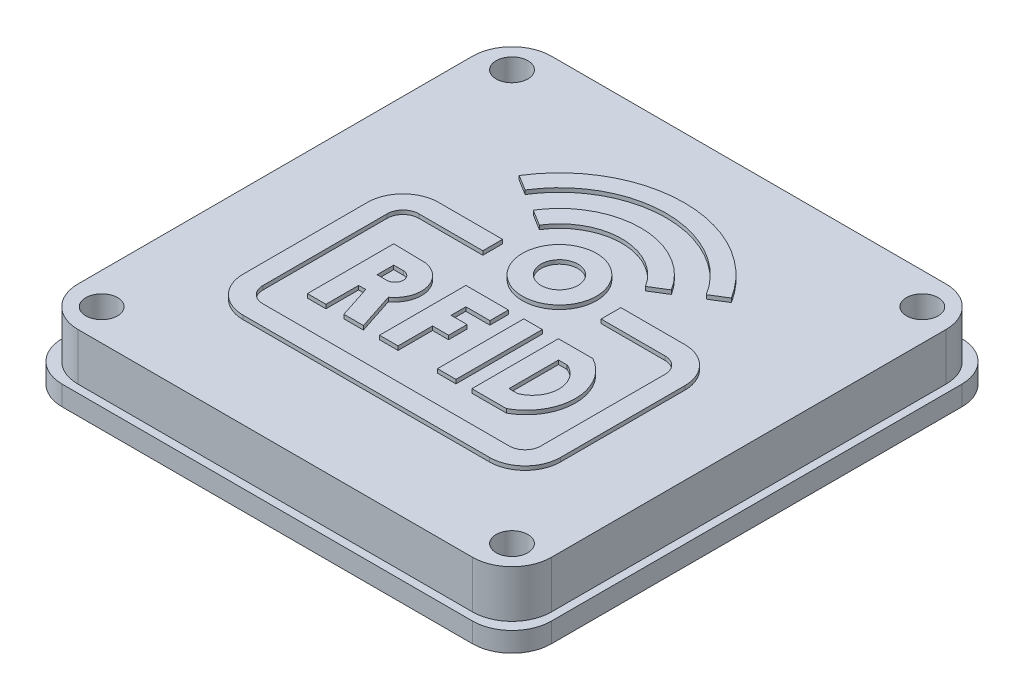
SolidWorks part; units mm, degrees
ref_plane "Front Plane" through (0, 0, 0) normal (0, 0, 1) x (1, 0, 0)
ref_plane "Top Plane" through (0, 0, 0) normal (0, 1, 0) x (1, 0, 0)
ref_plane "Right Plane" through (0, 0, 0) normal (1, 0, 0) x (0, 0, -1)
sketch "Sketch1" plane through (0, 0, 0) normal (0, 1, 0) x (1, 0, 0)
  line L1 (-60, 60) -> (60, 60)
  line L2 (-60, 60) -> (-60, -60)
  line L3 (-60, -60) -> (60, -60)
  line L4 (60, 60) -> (60, -60)
  line L5 (-60, 60) -> (60, -60) construction
  line L6 (-60, -60) -> (60, 60) construction
  point P0 (0, 0)
  dimension "D1" = 120
  dimension "D2" = 120
extrude "Boss-Extrude1" add sketch "Sketch1" along normal blind 17
shell "Shell1" thickness 3
sketch "Sketch2" plane through (0, 0, 0) normal (0, -1, 0) x (1, 0, 0)
  line L0 (60, -60) -> (-60, -60) construction
  line L1 (60, 60) -> (60, -60) construction
  line L2 (-60, 60) -> (60, 60) construction
  line L3 (-60, -60) -> (-60, 60) construction
  line L4 (60, -60) -> (-60, -60)
  line L5 (60, 60) -> (60, -60)
  line L6 (-60, 60) -> (60, 60)
  line L7 (-60, -60) -> (-60, 60)
  line L8 (-62, -62) -> (-62, 62)
  line L9 (-62, 62) -> (62, 62)
  line L10 (62, 62) -> (62, -62)
  line L11 (62, -62) -> (-62, -62)
  dimension "D1" = 2
extrude "Boss-Extrude2" add sketch "Sketch2" against normal blind 5
sketch "Sketch3" plane through (0, 17, 0) normal (0, 1, 0) x (1, 0, 0)
  line L0 (0, 60) -> (0, -60) construction
  line L1 (60, 60) -> (-60, 60) construction
  line L2 (-60, -60) -> (60, -60) construction
  line L3 (-60, 0) -> (60, 0) construction
  line L4 (-60, 60) -> (-60, -60) construction
  line L5 (60, 60) -> (60, -60) construction
  line L6 (-60, 52) -> (-52, 52) construction
  line L19 (-60, -60) -> (-60, 60) construction
  line L22 (-52, 52) -> (-52, 60) construction
  circle A4 centre (-52, 52) radius 4.02
  circle A5 centre (52, 52) radius 4.02
  circle A6 centre (52, -52) radius 4.02
  circle A7 centre (-52, -52) radius 4.02
  dimension "D1" = 8.04
  dimension "D3" = 8
  dimension "D2" = 8
sketch "Sketch4" plane through (0, 14, 0) normal (0, -1, 0) x (1, 0, 0)
  line L0 (-52, 60) -> (-52, 52) construction
  line L1 (60, 60) -> (-60, 60) construction
  line L10 (-52, 52) -> (-60, 52) construction
  line L11 (-60, 60) -> (-60, -60) construction
  line L12 (-57, 42.98) -> (-57, 57)
  line L14 (-57, 57) -> (-42.98, 57)
  line L16 (-55, 44.98) -> (-52, 44.98)
  line L17 (-44.98, 52) -> (-44.98, 55)
  line L18 (0, 60) -> (0, -60) construction
  line L19 (57, 42.98) -> (57, 57)
  line L20 (60, 0) -> (-60, 0) construction
  line L21 (55, 44.98) -> (52, 44.98)
  line L22 (44.98, 52) -> (44.98, 55)
  line L23 (57, 57) -> (42.98, 57)
  line L24 (55, -44.98) -> (52, -44.98)
  line L25 (44.98, -52) -> (44.98, -55)
  line L26 (57, -57) -> (42.98, -57)
  line L27 (57, -42.98) -> (57, -57)
  line L28 (-57, -42.98) -> (-57, -57)
  line L29 (-55, -44.98) -> (-52, -44.98)
  line L30 (-44.98, -52) -> (-44.98, -55)
  line L31 (-57, -57) -> (-42.98, -57)
  circle A8 centre (-52, 52) radius 4.02
  arc A9 (-52, 44.98) -> (-44.98, 52) centre (-52, 52) ccw
  arc A10 (-57, 42.98) -> (-55, 44.98) centre (-55, 42.98) cw
  arc A11 (-42.98, 57) -> (-44.98, 55) centre (-42.98, 55) ccw
  circle A12 centre (-52, 52) radius 7.02 construction
  arc A13 (57, 42.98) -> (55, 44.98) centre (55, 42.98) ccw
  arc A14 (52, 44.98) -> (44.98, 52) centre (52, 52) cw
  arc A15 (42.98, 57) -> (44.98, 55) centre (42.98, 55) cw
  circle A16 centre (52, 52) radius 4.02
  arc A17 (57, -42.98) -> (55, -44.98) centre (55, -42.98) cw
  arc A18 (52, -44.98) -> (44.98, -52) centre (52, -52) ccw
  arc A19 (42.98, -57) -> (44.98, -55) centre (42.98, -55) ccw
  circle A20 centre (52, -52) radius 4.02
  arc A21 (-57, -42.98) -> (-55, -44.98) centre (-55, -42.98) ccw
  arc A22 (-52, -44.98) -> (-44.98, -52) centre (-52, -52) cw
  arc A23 (-42.98, -57) -> (-44.98, -55) centre (-42.98, -55) cw
  circle A24 centre (-52, -52) radius 4.02
  dimension "D1" = 8
  dimension "D4" = 3
  dimension "D3" = 8.04
  dimension "D5" = 2
  dimension "D2" = 8
extrude "Boss-Extrude3" add sketch "Sketch4" along normal blind 14
extrude "Cut-Extrude1" cut sketch "Sketch3" against normal blind 3
fillet "Fillet1" radius 10 8 edges at (-60, 11, -60) (-62, 2.5, -62) (-60, 11, 60) (-62, 2.5, 62) (62, 2.5, -62) (60, 11, -60) (62, 2.5, 62) (60, 11, 60)
sketch "Sketch8" plane through (0, 17, 0) normal (0, 1, 0) x (1, 0, 0)
  point P0 (0, -31.9271)
  point P2 (0, 0)
  line B0 (-25.73, 30.2815) -> (-26.8861, 28.7192)
  line B1 (-26.8861, 28.7192) -> (-24.9958, 27.5006)
  line B2 (24.996, 27.485) -> (26.8863, 28.7036)
  line B3 (26.8863, 28.7036) -> (25.6834, 30.3127)
  line B4 (15.7787, 21.5173) -> (17.6534, 22.7202)
  line B5 (17.6534, 22.7202) -> (17.4035, 23.1264)
  line B6 (-2.1871, 32.2655) -> (-2.187, 32.2655)
  line B7 (39.9622, -11.7272) -> (39.9154, 4.0045)
  line B8 (39.9154, 4.0045) -> (39.4935, 5.2699)
  line B9 (23.2462, 12.3156) -> (14.9976, 12.3781)
  line B10 (14.9976, 12.3781) -> (14.9976, 10.0347)
  line B11 (14.9976, 10.0347) -> (14.9976, 7.6913)
  line B12 (14.9976, 7.6913) -> (23.0119, 7.6445)
  line B13 (23.0119, 7.6445) -> (31.0105, 7.5976)
  line B14 (31.0105, 7.5976) -> (32.026, 7.1133)
  line B15 (34.8068, 4.3951) -> (35.2286, 3.5358)
  line B16 (35.2286, 3.5358) -> (35.2286, -12.1647)
  line B17 (35.2286, -12.1647) -> (35.2286, -27.8653)
  line B18 (35.2286, -27.8653) -> (34.713, -28.912)
  line B19 (32.0416, -31.5209) -> (31.1667, -31.9271)
  line B20 (31.1667, -31.9271) -> (0, -31.9271)
  line B21 (0, -31.9271) -> (-31.1667, -31.9271)
  line B22 (-31.1667, -31.9271) -> (-32.0259, -31.5209)
  line B23 (-34.713, -28.912) -> (-35.2286, -27.8653)
  line B24 (-35.2286, -27.8653) -> (-35.2286, -12.1647)
  line B25 (-35.2286, -12.1647) -> (-35.2286, 3.5358)
  line B26 (-35.2286, 3.5358) -> (-34.7911, 4.4263)
  line B27 (-32.0259, 7.1133) -> (-31.0105, 7.5976)
  line B28 (-31.0105, 7.5976) -> (-22.9962, 7.6445)
  line B29 (-22.9962, 7.6445) -> (-14.9975, 7.6913)
  line B30 (-14.9975, 7.6913) -> (-14.9975, 10.0347)
  line B31 (-14.9975, 10.0347) -> (-14.9975, 12.3625)
  line B32 (-14.9975, 12.3625) -> (-22.6837, 12.3468)
  line B33 (-31.1667, 12.2062) -> (-31.1666, 12.2063)
  line B34 (-27.8078, -13.102) -> (-27.8078, -24.0377)
  line B35 (-27.8078, -24.0377) -> (-25.4644, -24.0377)
  line B36 (-25.4644, -24.0377) -> (-23.121, -24.0377)
  line B37 (-23.121, -24.0377) -> (-23.121, -19.8977)
  line B38 (-23.121, -19.8977) -> (-23.121, -15.7578)
  line B39 (-23.121, -15.7578) -> (-22.2149, -15.7578)
  line B40 (-22.2149, -15.7578) -> (-21.3088, -15.7578)
  line B41 (-21.3088, -15.7578) -> (-19.9809, -19.8509)
  line B42 (-19.9809, -19.8509) -> (-18.653, -23.9596)
  line B43 (-18.653, -23.9596) -> (-16.1847, -24.0065)
  line B44 (-15.2942, -19.101) -> (-16.7627, -14.5705)
  line B45 (-16.7627, -14.5705) -> (-15.9815, -13.7894)
  line B46 (-24.152, -2.1663) -> (-27.8077, -2.1663)
  line B47 (-27.8077, -2.1663) -> (-27.8077, -13.102)
  line B48 (-21.715, -11.0711) -> (-23.1211, -11.0711)
  line B49 (-23.1211, -11.0711) -> (-23.1211, -8.9621)
  line B50 (-23.1211, -8.9621) -> (-23.1211, -6.853)
  line B51 (-23.1211, -6.853) -> (-21.8244, -6.853)
  line B52 (-9.5295, -13.102) -> (-9.5295, -24.0377)
  line B53 (-9.5295, -24.0377) -> (-7.1862, -24.0377)
  line B54 (-7.1862, -24.0377) -> (-4.8428, -24.0377)
  line B55 (-4.8428, -24.0377) -> (-4.8428, -19.6634)
  line B56 (-4.8428, -19.6634) -> (-4.8428, -15.2891)
  line B57 (-4.8428, -15.2891) -> (-2.8119, -15.2891)
  line B58 (-2.8119, -15.2891) -> (-0.781, -15.2891)
  line B59 (-0.781, -15.2891) -> (-0.781, -12.9457)
  line B60 (-0.781, -12.9457) -> (-0.781, -10.6023)
  line B61 (-0.781, -10.6023) -> (-2.8119, -10.6023)
  line B62 (-2.8119, -10.6023) -> (-4.8428, -10.6023)
  line B63 (-4.8428, -10.6023) -> (-4.8428, -8.7277)
  line B64 (-4.8428, -8.7277) -> (-4.8428, -6.853)
  line B65 (-4.8428, -6.853) -> (-1.7964, -6.853)
  line B66 (-1.7964, -6.853) -> (1.25, -6.853)
  line B67 (1.25, -6.853) -> (1.25, -4.5096)
  line B68 (1.25, -4.5096) -> (1.25, -2.1662)
  line B69 (1.25, -2.1662) -> (-4.1397, -2.1662)
  line B70 (-4.1397, -2.1662) -> (-9.5295, -2.1662)
  line B71 (-9.5295, -2.1662) -> (-9.5295, -13.1019)
  line B72 (5.1555, -13.102) -> (5.1555, -24.0377)
  line B73 (5.1555, -24.0377) -> (7.4989, -24.0377)
  line B74 (7.4989, -24.0377) -> (9.8423, -24.0377)
  line B75 (9.8423, -24.0377) -> (9.8423, -13.102)
  line B76 (9.8423, -13.102) -> (9.8423, -2.1663)
  line B77 (9.8423, -2.1663) -> (7.4989, -2.1663)
  line B78 (7.4989, -2.1663) -> (5.1555, -2.1663)
  line B79 (5.1555, -2.1663) -> (5.1555, -13.102)
  line B80 (13.904, -13.102) -> (13.904, -24.0689)
  line B81 (13.904, -24.0689) -> (17.7784, -24.0065)
  line B82 (17.7784, -2.1976) -> (13.904, -2.1351)
  line B83 (13.904, -2.1351) -> (13.904, -13.102)
  line B84 (19.4188, -19.351) -> (18.5908, -19.351)
  line B85 (18.5908, -19.351) -> (18.5908, -13.0864)
  line B86 (18.5908, -13.0864) -> (18.5908, -6.8061)
  line B87 (18.5908, -6.8061) -> (19.8094, -6.8999)
  spline B88 degree 3 poles (-2.7338, 43.2012) (-12.1385, 42.217) (-20.2153, 37.6864) (-25.73, 30.2815) knots 0 0 0 0 0.071429 0.071429 0.071429 0.071429
  spline B89 degree 3 poles (-24.9958, 27.5006) (-23.9491, 26.8133) (-23.043, 26.2665) (-22.9805, 26.2665) knots 0.214286 0.214286 0.214286 0.214286 0.285714 0.285714 0.285714 0.285714
  spline B90 degree 3 poles (-22.9805, 26.2665) (-22.9024, 26.2665) (-22.4025, 26.8757) (-21.8557, 27.6257) knots 0.285714 0.285714 0.285714 0.285714 0.357143 0.357143 0.357143 0.357143
  spline B91 degree 3 poles (-21.8557, 27.6257) (-19.403, 31.0157) (-15.7161, 34.0152) (-11.6386, 35.968) knots 0.357143 0.357143 0.357143 0.357143 0.428571 0.428571 0.428571 0.428571
  spline B92 degree 3 poles (-11.6386, 35.968) (-0.0624, 41.5296) (14.0915, 38.0302) (21.7777, 27.7194) knots 0.428571 0.428571 0.428571 0.428571 0.5 0.5 0.5 0.5
  spline B93 degree 3 poles (21.7777, 27.7194) (22.3714, 26.9226) (22.9182, 26.2665) (22.9963, 26.2665) knots 0.5 0.5 0.5 0.5 0.571429 0.571429 0.571429 0.571429
  spline B94 degree 3 poles (22.9963, 26.2665) (23.0588, 26.2665) (23.9649, 26.8133) (24.996, 27.485) knots 0.571429 0.571429 0.571429 0.571429 0.642857 0.642857 0.642857 0.642857
  spline B95 degree 3 poles (25.6834, 30.3127) (20.6373, 37.0772) (13.3417, 41.514) (4.9993, 42.9044) knots 0.785714 0.785714 0.785714 0.785714 0.857143 0.857143 0.857143 0.857143
  spline B96 degree 3 poles (4.9993, 42.9044) (3.5776, 43.1387) (-1.4371, 43.3418) (-2.7338, 43.2012) knots 0.857143 0.857143 0.857143 0.857143 0.928571 0.928571 0.928571 0.928571
  spline B97 degree 3 poles (-2.187, 32.2655) (-6.905, 31.6718) (-11.2168, 29.6722) (-14.5131, 26.5008) knots 0 0 0 0 0.066667 0.066667 0.066667 0.066667
  spline B98 degree 3 poles (-14.5131, 26.5008) (-15.9191, 25.1417) (-17.747, 22.8452) (-17.5439, 22.689) knots 0.066667 0.066667 0.066667 0.066667 0.133333 0.133333 0.133333 0.133333
  spline B99 degree 3 poles (-17.5439, 22.689) (-17.1221, 22.3453) (-13.9351, 20.33) (-13.8101, 20.33) knots 0.133333 0.133333 0.133333 0.133333 0.2 0.2 0.2 0.2
  spline B100 degree 3 poles (-13.8101, 20.33) (-13.732, 20.33) (-13.279, 20.8299) (-12.8259, 21.4392) knots 0.2 0.2 0.2 0.2 0.266667 0.266667 0.266667 0.266667
  spline B101 degree 3 poles (-12.8259, 21.4392) (-10.7481, 24.1575) (-7.4362, 26.2821) (-3.8274, 27.2195) knots 0.266667 0.266667 0.266667 0.266667 0.333333 0.333333 0.333333 0.333333
  spline B102 degree 3 poles (-3.8274, 27.2195) (-1.7965, 27.735) (1.8123, 27.735) (3.8119, 27.2195) knots 0.333333 0.333333 0.333333 0.333333 0.4 0.4 0.4 0.4
  spline B103 degree 3 poles (3.8119, 27.2195) (7.452, 26.2665) (10.5296, 24.3137) (12.7011, 21.5798) knots 0.4 0.4 0.4 0.4 0.466667 0.466667 0.466667 0.466667
  spline B104 degree 3 poles (12.7011, 21.5798) (13.2167, 20.9393) (13.6853, 20.3768) (13.7634, 20.3612) knots 0.466667 0.466667 0.466667 0.466667 0.533333 0.533333 0.533333 0.533333
  spline B105 degree 3 poles (13.7634, 20.3612) (13.8416, 20.3299) (14.7477, 20.8455) (15.7787, 21.5173) knots 0.533333 0.533333 0.533333 0.533333 0.6 0.6 0.6 0.6
  spline B106 degree 3 poles (17.4035, 23.1264) (16.7629, 24.1106) (15.5288, 25.5479) (14.3571, 26.6414) knots 0.733333 0.733333 0.733333 0.733333 0.8 0.8 0.8 0.8
  spline B107 degree 3 poles (14.3571, 26.6414) (11.5294, 29.2972) (7.8425, 31.2032) (4.0619, 31.9687) knots 0.8 0.8 0.8 0.8 0.866667 0.866667 0.866667 0.866667
  spline B108 degree 3 poles (4.0619, 31.9687) (2.9058, 32.203) (-1.1404, 32.3905) (-2.1871, 32.2655) knots 0.866667 0.866667 0.866667 0.866667 0.933333 0.933333 0.933333 0.933333
  spline B109 degree 3 poles (4.4212, 20.2988) (2.3591, 21.3767) (-0.1249, 21.6735) (-2.312, 21.1111) knots 0.875 0.875 0.875 0.875 1 1 1 1
  spline B110 degree 3 poles (8.4049, 16.112) (7.6238, 17.7367) (5.9366, 19.5021) (4.4212, 20.2988) knots 0.75 0.75 0.75 0.75 0.875 0.875 0.875 0.875
  spline B111 degree 3 poles (9.3423, 11.4565) (9.4361, 13.2218) (9.1861, 14.4716) (8.4049, 16.112) knots 0.625 0.625 0.625 0.625 0.75 0.75 0.75 0.75
  spline B112 degree 3 poles (2.2654, 2.9111) (6.2335, 3.9109) (9.108, 7.379) (9.3423, 11.4565) knots 0.5 0.5 0.5 0.5 0.625 0.625 0.625 0.625
  spline B113 degree 3 poles (-2.2652, 2.9111) (-1.0779, 2.6142) (1.078, 2.6142) (2.2654, 2.9111) knots 0.375 0.375 0.375 0.375 0.5 0.5 0.5 0.5
  spline B114 degree 3 poles (-9.3421, 11.4565) (-9.1077, 7.379) (-6.2489, 3.9265) (-2.2652, 2.9111) knots 0.25 0.25 0.25 0.25 0.375 0.375 0.375 0.375
  spline B115 degree 3 poles (-6.6082, 18.5959) (-8.5922, 16.6275) (-9.4983, 14.2685) (-9.3421, 11.4565) knots 0.125 0.125 0.125 0.125 0.25 0.25 0.25 0.25
  spline B116 degree 3 poles (-2.312, 21.1111) (-4.0149, 20.658) (-5.2334, 19.955) (-6.6082, 18.5959) knots 0 0 0 0 0.125 0.125 0.125 0.125
  spline B117 degree 3 poles (-4.6554, 12.3625) (-4.421, 15.487) (-1.2966, 17.518) (1.6092, 16.4244) knots 0.8 0.8 0.8 0.8 1 1 1 1
  spline B118 degree 3 poles (-3.2962, 8.7538) (-4.3898, 9.8629) (-4.7647, 10.8315) (-4.6554, 12.3625) knots 0.6 0.6 0.6 0.6 0.8 0.8 0.8 0.8
  spline B119 degree 3 poles (1.6561, 7.6289) (-0.1717, 7.004) (-1.9527, 7.4102) (-3.2962, 8.7538) knots 0.4 0.4 0.4 0.4 0.6 0.6 0.6 0.6
  spline B120 degree 3 poles (4.4525, 10.4722) (4.0776, 9.3474) (2.734, 7.9883) (1.6561, 7.6289) knots 0.2 0.2 0.2 0.2 0.4 0.4 0.4 0.4
  spline B121 degree 3 poles (1.6092, 16.4244) (3.9994, 15.5339) (5.2492, 12.8937) (4.4525, 10.4722) knots 0 0 0 0 0.2 0.2 0.2 0.2
  spline B122 degree 3 poles (-31.1666, 12.2063) (-32.4633, 12.0032) (-33.2913, 11.7377) (-34.5254, 11.0971) knots 0 0 0 0 0.02439 0.02439 0.02439 0.02439
  spline B123 degree 3 poles (-34.5254, 11.0971) (-37.2593, 9.6911) (-39.1184, 7.2071) (-39.7433, 4.192) knots 0.02439 0.02439 0.02439 0.02439 0.04878 0.04878 0.04878 0.04878
  spline B124 degree 3 poles (-39.7433, 4.192) (-40.1026, 2.4735) (-40.1183, -26.9591) (-39.7589, -28.6463) knots 0.04878 0.04878 0.04878 0.04878 0.073171 0.073171 0.073171 0.073171
  spline B125 degree 3 poles (-39.7589, -28.6463) (-38.9778, -32.3957) (-35.6971, -35.6764) (-31.9477, -36.4575) knots 0.073171 0.073171 0.073171 0.073171 0.097561 0.097561 0.097561 0.097561
  spline B126 degree 3 poles (-31.9477, -36.4575) (-30.3074, -36.8012) (30.3075, -36.8012) (31.9479, -36.4575) knots 0.097561 0.097561 0.097561 0.097561 0.121951 0.121951 0.121951 0.121951
  spline B127 degree 3 poles (31.9479, -36.4575) (34.8224, -35.8639) (37.5876, -33.708) (38.8842, -31.0678) knots 0.121951 0.121951 0.121951 0.121951 0.146341 0.146341 0.146341 0.146341
  spline B128 degree 3 poles (38.8842, -31.0678) (40.0403, -28.6932) (40.0091, -29.3806) (39.9622, -11.7272) knots 0.146341 0.146341 0.146341 0.146341 0.170732 0.170732 0.170732 0.170732
  spline B129 degree 3 poles (39.4935, 5.2699) (38.3687, 8.5663) (35.8379, 10.9721) (32.4166, 11.9875) knots 0.219512 0.219512 0.219512 0.219512 0.243902 0.243902 0.243902 0.243902
  spline B130 degree 3 poles (32.4166, 11.9875) (31.5886, 12.2219) (30.5575, 12.2688) (23.2462, 12.3156) knots 0.243902 0.243902 0.243902 0.243902 0.268293 0.268293 0.268293 0.268293
  spline B131 degree 3 poles (32.026, 7.1133) (33.2446, 6.5353) (34.2288, 5.5667) (34.8068, 4.3951) knots 0.414634 0.414634 0.414634 0.414634 0.439024 0.439024 0.439024 0.439024
  spline B132 degree 3 poles (34.713, -28.912) (34.1194, -30.1149) (33.2758, -30.9429) (32.0416, -31.5209) knots 0.536585 0.536585 0.536585 0.536585 0.560976 0.560976 0.560976 0.560976
  spline B133 degree 3 poles (-32.0259, -31.5209) (-33.307, -30.9117) (-34.135, -30.1149) (-34.713, -28.912) knots 0.658537 0.658537 0.658537 0.658537 0.682927 0.682927 0.682927 0.682927
  spline B134 degree 3 poles (-34.7911, 4.4263) (-34.2131, 5.5979) (-33.2601, 6.5197) (-32.0259, 7.1133) knots 0.780488 0.780488 0.780488 0.780488 0.804878 0.804878 0.804878 0.804878
  spline B135 degree 3 poles (-22.6837, 12.3468) (-26.9174, 12.3312) (-30.7293, 12.2687) (-31.1667, 12.2062) knots 0.95122 0.95122 0.95122 0.95122 0.97561 0.97561 0.97561 0.97561
  spline B136 degree 3 poles (-16.1847, -24.0065) (-14.2319, -24.0377) (-13.732, -24.0065) (-13.7788, -23.8502) knots 0.5 0.5 0.5 0.5 0.55 0.55 0.55 0.55
  spline B137 degree 3 poles (-13.7788, -23.8502) (-13.8101, -23.7409) (-14.4975, -21.6006) (-15.2942, -19.101) knots 0.55 0.55 0.55 0.55 0.6 0.6 0.6 0.6
  spline B138 degree 3 poles (-15.9815, -13.7894) (-13.7475, -11.5554) (-13.2788, -8.4934) (-14.763, -5.7751) knots 0.7 0.7 0.7 0.7 0.75 0.75 0.75 0.75
  spline B139 degree 3 poles (-14.763, -5.7751) (-15.6691, -4.1347) (-17.7, -2.6975) (-19.6684, -2.3225) knots 0.75 0.75 0.75 0.75 0.8 0.8 0.8 0.8
  spline B140 degree 3 poles (-19.6684, -2.3225) (-20.1371, -2.2444) (-22.1524, -2.1663) (-24.152, -2.1663) knots 0.8 0.8 0.8 0.8 0.85 0.85 0.85 0.85
  spline B141 degree 3 poles (-19.8872, -7.1655) (-18.2, -7.9153) (-18.2, -9.9775) (-19.8716, -10.8524) knots 0 0 0 0 0.125 0.125 0.125 0.125
  spline B142 degree 3 poles (-19.8716, -10.8524) (-20.1372, -10.993) (-20.7933, -11.0711) (-21.715, -11.0711) knots 0.125 0.125 0.125 0.125 0.25 0.25 0.25 0.25
  spline B143 degree 3 poles (-21.8244, -6.853) (-20.9026, -6.853) (-20.3559, -6.9468) (-19.8872, -7.1655) knots 0.75 0.75 0.75 0.75 0.875 0.875 0.875 0.875
  spline B144 degree 3 poles (17.7784, -24.0065) (21.4653, -23.944) (21.684, -23.9283) (22.6838, -23.5378) knots 0.2 0.2 0.2 0.2 0.3 0.3 0.3 0.3
  spline B145 degree 3 poles (22.6838, -23.5378) (24.9335, -22.6786) (26.6988, -21.0538) (27.7768, -18.8355) knots 0.3 0.3 0.3 0.3 0.4 0.4 0.4 0.4
  spline B146 degree 3 poles (27.7768, -18.8355) (28.5891, -17.1795) (28.9016, -15.9141) (29.0109, -13.8675) knots 0.4 0.4 0.4 0.4 0.5 0.5 0.5 0.5
  spline B147 degree 3 poles (29.0109, -13.8675) (29.3077, -8.3684) (26.9644, -4.166) (22.7463, -2.6507) knots 0.5 0.5 0.5 0.5 0.6 0.6 0.6 0.6
  spline B148 degree 3 poles (22.7463, -2.6507) (21.6996, -2.2757) (21.434, -2.2601) (17.7784, -2.1976) knots 0.6 0.6 0.6 0.6 0.7 0.7 0.7 0.7
  spline B149 degree 3 poles (21.6528, -7.3061) (22.4339, -7.7122) (22.6526, -7.8997) (23.1681, -8.5871) knots 0 0 0 0 0.111111 0.111111 0.111111 0.111111
  spline B150 degree 3 poles (23.1681, -8.5871) (23.8399, -9.4776) (24.2304, -10.8055) (24.3242, -12.5552) knots 0.111111 0.111111 0.111111 0.111111 0.222222 0.222222 0.222222 0.222222
  spline B151 degree 3 poles (24.3242, -12.5552) (24.5585, -16.7576) (22.6838, -19.351) (19.4188, -19.351) knots 0.222222 0.222222 0.222222 0.222222 0.333333 0.333333 0.333333 0.333333
  spline B152 degree 3 poles (19.8094, -6.8999) (20.6217, -6.9467) (21.2466, -7.0873) (21.6528, -7.3061) knots 0.777778 0.777778 0.777778 0.777778 0.888889 0.888889 0.888889 0.888889
sketch_block_instance "RFID-1"
sketch_block "RFID"
sketch "Sketch9" plane through (0, 17, 0) normal (0, 1, 0) x (1, 0, 0)
  line L0 (-13.443, 20.3759) -> (-17.5048, 22.8968)
  line L1 (-40.2286, -27.9271) -> (-40.2286, 3.5976)
  line L2 (-31.2286, 12.5976) -> (-14.9884, 12.5976)
  line L3 (0, 16.7233) -> (0, 7.3422) construction
  line L4 (13.4452, 20.3725) -> (17.5076, 22.8923)
  line L6 (-22.9676, 26.2872) -> (-26.8861, 28.7192)
  line L7 (22.9713, 26.2813) -> (26.8904, 28.7123)
  line L8 (-35.2286, -27.9271) -> (-35.2286, 3.5976)
  line L9 (-31.2286, 7.5976) -> (-14.9884, 7.5976)
  line L10 (35.2286, 3.5976) -> (35.2286, -27.9271)
  line L11 (31.2286, -31.9271) -> (-31.2286, -31.9271)
  line L12 (40.2286, 3.5976) -> (40.2286, -27.9271)
  line L13 (31.2286, -36.9271) -> (-31.2286, -36.9271)
  line L14 (-14.9884, 12.5976) -> (-14.9884, 7.5976)
  line L15 (14.9884, 12.5976) -> (14.9884, 7.5976)
  line L16 (14.9884, 12.5976) -> (31.2286, 12.5976)
  line L17 (-31.2286, 12.5976) -> (31.2286, 12.5976) construction
  line L18 (14.9884, 7.5976) -> (31.2286, 7.5976)
  line L19 (-31.2286, 7.5976) -> (31.2286, 7.5976) construction
  line L20 (-27.8078, -24.0377) -> (-27.8077, -2.1663)
  line L21 (-27.8077, -2.1663) -> (-19.6684, -2.3225)
  line L22 (-27.8078, -24.0377) -> (-23.121, -24.0377)
  line L23 (-23.121, -24.0377) -> (-23.121, -15.7578)
  line L24 (-23.121, -15.7578) -> (-21.3088, -15.7578)
  line L25 (-21.3088, -15.7578) -> (-18.653, -23.9596)
  line L26 (-18.653, -23.9596) -> (-13.6948, -23.9596)
  line L27 (-13.6948, -23.9596) -> (-16.7627, -14.5705)
  line L28 (-23.1211, -6.853) -> (-23.1211, -11.0711)
  line L29 (-23.1211, -6.853) -> (-20.6881, -6.853)
  line L30 (-23.1211, -11.0711) -> (-20.6881, -11.0711)
  line L31 (-9.5295, -2.1662) -> (-9.5295, -24.0377)
  line L32 (-9.5295, -24.0377) -> (-4.8428, -24.0377)
  line L33 (-4.8428, -24.0377) -> (-4.8428, -15.2891)
  line L34 (-4.8428, -15.2891) -> (-0.781, -15.2891)
  line L35 (-0.781, -15.2891) -> (-0.781, -10.6023)
  line L36 (-0.781, -10.6023) -> (-4.8428, -10.6023)
  line L37 (-4.8428, -10.6023) -> (-4.8428, -6.853)
  line L38 (-4.8428, -6.853) -> (1.25, -6.853)
  line L39 (1.25, -6.853) -> (1.25, -2.1662)
  line L40 (1.25, -2.1662) -> (-9.5295, -2.1662)
  line L41 (5.1555, -2.1663) -> (5.1555, -24.0377)
  line L42 (5.1555, -24.0377) -> (9.8423, -24.0377)
  line L43 (9.8423, -24.0377) -> (9.8423, -2.1663)
  line L44 (9.8423, -2.1663) -> (5.1555, -2.1663)
  line L45 (13.904, -2.1351) -> (13.904, -24.0689)
  line L46 (13.904, -24.0689) -> (22.6215, -24.0689)
  line L48 (22.6215, -2.1351) -> (13.904, -2.1351)
  line L49 (18.5908, -6.8061) -> (18.5908, -19.351)
  line L50 (18.5908, -19.351) -> (20.8086, -19.351)
  line L52 (20.8086, -6.8061) -> (18.5908, -6.8061)
  arc A0 (-26.8861, 28.7192) -> (26.8904, 28.7123) centre (0, 12.0327) cw
  arc A1 (-13.443, 20.3759) -> (13.4452, 20.3725) centre (0, 12.0327) cw
  arc A2 (-17.5048, 22.8968) -> (17.5076, 22.8923) centre (0, 12.0327) cw
  arc A3 (-22.9676, 26.2872) -> (22.9713, 26.2813) centre (0, 12.0327) cw
  circle A4 centre (0, 12.0327) radius 4.6906
  circle A5 centre (0, 12.0327) radius 9.3988
  arc A6 (31.2286, 7.5976) -> (35.2286, 3.5976) centre (31.2286, 3.5976) cw
  arc A7 (35.2286, -27.9271) -> (31.2286, -31.9271) centre (31.2286, -27.9271) cw
  arc A8 (-35.2286, -27.9271) -> (-31.2286, -31.9271) centre (-31.2286, -27.9271) ccw
  arc A9 (-35.2286, 3.5976) -> (-31.2286, 7.5976) centre (-31.2286, 3.5976) cw
  arc A10 (-40.2286, 3.5976) -> (-31.2286, 12.5976) centre (-31.2286, 3.5976) cw
  arc A11 (31.2286, 12.5976) -> (40.2286, 3.5976) centre (31.2286, 3.5976) cw
  arc A12 (40.2286, -27.9271) -> (31.2286, -36.9271) centre (31.2286, -27.9271) cw
  arc A13 (-40.2286, -27.9271) -> (-31.2286, -36.9271) centre (-31.2286, -27.9271) ccw
  arc A14 (-19.6684, -2.3225) -> (-16.7627, -14.5705) centre (-20.6881, -9.0331) cw
  arc A15 (-20.6881, -6.853) -> (-20.6881, -11.0711) centre (-20.6881, -8.9621) cw
  arc A16 (22.6215, -2.1351) -> (22.6215, -24.0689) centre (16.7454, -13.102) cw
  arc A17 (20.8086, -6.8061) -> (20.8086, -19.351) centre (18.2291, -13.0786) cw
  spline S0 degree 3 poles (-4.6554, 12.3625) (-4.421, 15.487) (-1.2966, 17.518) (1.6092, 16.4244) knots 0.8 0.8 0.8 0.8 1 1 1 1 construction
  spline S1 degree 3 poles (1.6561, 7.6289) (-0.1717, 7.004) (-1.9527, 7.4102) (-3.2962, 8.7538) knots 0.4 0.4 0.4 0.4 0.6 0.6 0.6 0.6 construction
  spline S2 degree 3 poles (-14.5131, 26.5008) (-15.9191, 25.1417) (-17.747, 22.8452) (-17.5439, 22.689) knots 0.066667 0.066667 0.066667 0.066667 0.133333 0.133333 0.133333 0.133333 construction
  dimension "D1" = 4
  dimension "D2" = 5
extrude "Boss-Extrude7" add sketch "Sketch9" along normal blind 1
